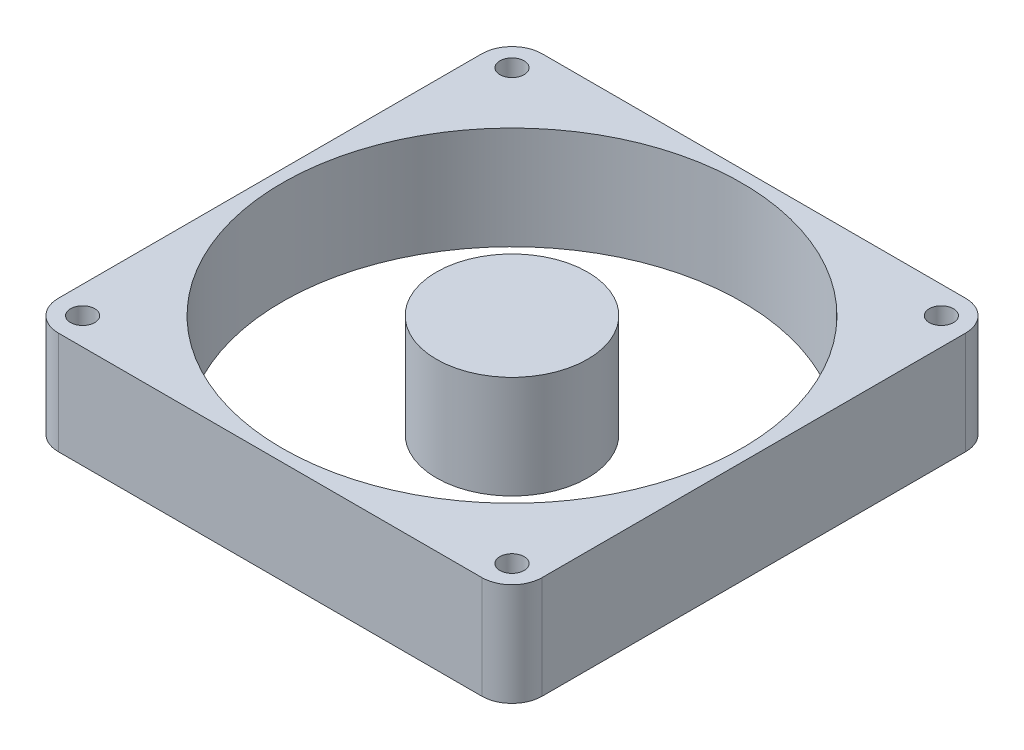
SolidWorks part; units mm, degrees
ref_plane "前视基准面" through (0, 0, 0) normal (0, 0, 1) x (1, 0, 0)
ref_plane "上视基准面" through (0, 0, 0) normal (0, 1, 0) x (1, 0, 0)
ref_plane "右视基准面" through (0, 0, 0) normal (1, 0, 0) x (0, 0, -1)
sketch "草图1" plane through (0, 0, 0) normal (0, 1, 0) x (1, 0, 0)
  line L0 (0, 74.7112) -> (0, -68.6123) construction
  line L1 (-35, 40) -> (35, 40)
  line L2 (-40, 35) -> (-40, -35)
  line L3 (-35, -40) -> (35, -40)
  line L4 (40, 35) -> (40, -35)
  line L5 (-53.6701, 0) -> (64.953, 0) construction
  arc A0 (40, 35) -> (35, 40) centre (35, 35) ccw
  arc A1 (-40, 35) -> (-35, 40) centre (-35, 35) cw
  arc A2 (-35, -40) -> (-40, -35) centre (-35, -35) cw
  arc A3 (40, -35) -> (35, -40) centre (35, -35) cw
  point P11 (40, 40)
  point P14 (-40, 40)
  point P17 (-40, -40)
  dimension "D3" = 5
  dimension "D4" = 5
  dimension "D1" = 80
  dimension "D2" = 80
extrude "拉伸1" add sketch "草图1" along normal blind 17
sketch "草图2" plane through (0, 17, 0) normal (0, 1, 0) x (-1, 0, 0)
  line L10 (-60.6024, 0) -> (52.7191, 0) construction
  line L11 (0, -57.861) -> (0, 57.0129) construction
  line L12 (-35, -38) -> (35, -38)
  line L13 (-38, 35) -> (-38, -35)
  line L14 (35, 38) -> (-35, 38)
  line L15 (38, -35) -> (38, 35)
  line L16 (-35, -38) -> (35, -38)
  line L17 (-38, 35) -> (-38, -35)
  line L18 (35, 38) -> (-35, 38)
  line L19 (38, -35) -> (38, 35)
  circle A8 centre (0, 0) radius 12.5
  arc A12 (-38, -35) -> (-35, -38) centre (-35, -35) ccw
  arc A13 (35, -38) -> (38, -35) centre (35, -35) ccw
  arc A14 (-35, 38) -> (-38, 35) centre (-35, 35) ccw
  arc A15 (38, 35) -> (35, 38) centre (35, 35) ccw
  arc A16 (-38, -35) -> (-35, -38) centre (-35, -35) ccw
  arc A17 (35, -38) -> (38, -35) centre (35, -35) ccw
  arc A18 (-35, 38) -> (-38, 35) centre (-35, 35) ccw
  arc A19 (38, 35) -> (35, 38) centre (35, 35) ccw
  dimension "D2" = 25
  dimension "D1" = 2
extrude "切除-拉伸1" cut sketch "草图2" against normal blind 17
sketch "草图3" plane through (0, 17, 0) normal (0, 1, 0) x (-1, 0, 0)
  line L0 (40, -35) -> (40, 35) construction
  line L1 (35, 40) -> (-35, 40) construction
  line L2 (-40, 35) -> (-40, -35) construction
  line L3 (-35, -40) -> (35, -40) construction
  line L4 (40, -35) -> (40, 35)
  line L5 (35, 40) -> (-35, 40)
  line L6 (-40, 35) -> (-40, -35)
  line L7 (-35, -40) -> (35, -40)
  circle A0 centre (0, 0) radius 38
  arc A1 (35, -40) -> (40, -35) centre (35, -35) ccw construction
  arc A2 (40, 35) -> (35, 40) centre (35, 35) ccw construction
  arc A3 (-35, 40) -> (-40, 35) centre (-35, 35) ccw construction
  arc A4 (-40, -35) -> (-35, -40) centre (-35, -35) ccw construction
  arc A5 (35, -40) -> (40, -35) centre (35, -35) ccw
  arc A6 (40, 35) -> (35, 40) centre (35, 35) ccw
  arc A7 (-35, 40) -> (-40, 35) centre (-35, 35) ccw
  arc A8 (-40, -35) -> (-35, -40) centre (-35, -35) ccw
  dimension "D1" = 76
extrude "拉伸3" add sketch "草图3" against normal up to surface (17 mm away) up to face at (0, 0, 0)
sketch "草图4" plane through (0, 17, 0) normal (0, 1, 0) x (-1, 0, 0)
  line L0 (-49.3843, 0) -> (58.2292, 0) construction
  line L1 (0, -54.1753) -> (0, 51.7798) construction
  circle A0 centre (-35.5, -35.5) radius 2
  circle A1 centre (-35.5, 35.5) radius 2
  circle A2 centre (35.5, 35.5) radius 2
  circle A3 centre (35.5, -35.5) radius 2
  dimension "D1" = 4
  dimension "D2" = 71
  dimension "D3" = 71
extrude "切除-拉伸2" cut sketch "草图4" against normal up to surface (17 mm away) up to face at (0, 0, 38)
